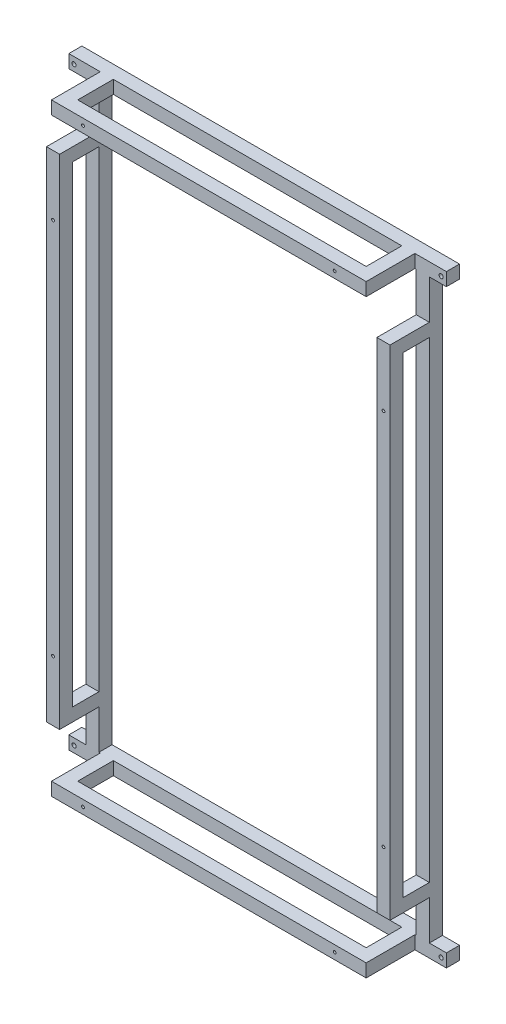
SolidWorks part; units mm, degrees
ref_plane "Plan de face" through (0, 0, 0) normal (0, 0, 1) x (1, 0, 0)
ref_plane "Plan de dessus" through (0, 0, 0) normal (0, 1, 0) x (1, 0, 0)
ref_plane "Plan de droite" through (0, 0, 0) normal (1, 0, 0) x (0, 0, -1)
sketch "Esquisse1" plane through (0, 0, 0) normal (0, 0, 1) x (1, 0, 0)
  line L1 (0, 0) -> (720, 0)
  line L2 (0, 0) -> (0, 25)
  line L3 (0, 25) -> (720, 25)
  line L4 (720, 0) -> (720, 25)
  line L5 (720, -1100) -> (0, -1100)
  line L6 (720, -1100) -> (720, -1125)
  line L7 (720, -1125) -> (0, -1125)
  line L8 (0, -1100) -> (0, -1125)
  point P9 (720, -1112.5)
  point P10 (720, 12.5)
  dimension "D1" = 25
  dimension "D2" = 720
  dimension "D3" = 720
  dimension "D4" = 0
  dimension "D5" = 25
  dimension "D6" = 1100
extrude "Boss.-Extru.1" add sketch "Esquisse1" along normal blind 25
sketch "Esquisse2" plane through (0, 0, 25) normal (0, 0, 1) x (1, 0, 0)
  line L0 (0, 25) -> (0, 0) construction
  line L1 (720, 0) -> (720, 25) construction
  line L2 (720, 25) -> (0, 25) construction
  line L4 (720, -1125) -> (720, -1100) construction
  line L5 (0, -1125) -> (720, -1125) construction
  line L6 (0, -1100) -> (0, -1125) construction
  circle A0 centre (10, 12.5) radius 4
  circle A1 centre (710, 12.5) radius 4
  circle A2 centre (710, -1112.5) radius 4
  circle A3 centre (10, -1112.5) radius 4
  point P22 (7.912, -1225)
  point P23 (0, 0)
  dimension "D2" = 8
  dimension "D3" = 8
  dimension "D7" = 8
  dimension "D8" = 8
  dimension "D1" = 700
  dimension "D4" = 10
  dimension "D5" = 10
  dimension "D6" = 12.5
  dimension "D9" = 10
  dimension "D10" = 12.5
  dimension "D11" = 10
  dimension "D12" = 12.5
extrude "Enlèv. mat.-Extru.1" cut sketch "Esquisse2" against normal blind 100 and the other way blind 25
sketch "Esquisse3" plane through (0, 0, 25) normal (0, 0, 1) x (1, 0, 0)
  line L0 (720, 25) -> (0, 25) construction
  line L1 (60, 25) -> (85, 25)
  line L2 (60, 25) -> (60, 0)
  line L3 (60, 0) -> (85, 0)
  line L4 (85, 25) -> (85, 0)
  line L5 (0, 0) -> (720, 0) construction
  line L6 (0, 25) -> (0, 0) construction
  line L7 (635, 0) -> (660, 0)
  line L8 (635, 0) -> (635, 25)
  line L9 (635, 25) -> (660, 25)
  line L10 (660, 0) -> (660, 25)
  line L11 (720, 0) -> (720, 25) construction
  line L12 (0, -1125) -> (720, -1125) construction
  line L13 (60, -1125) -> (85, -1125)
  line L14 (60, -1125) -> (60, -1100)
  line L15 (60, -1100) -> (85, -1100)
  line L16 (85, -1125) -> (85, -1100)
  line L17 (720, -1100) -> (0, -1100) construction
  line L19 (660, -1100) -> (635, -1100)
  line L20 (660, -1100) -> (660, -1125)
  line L21 (660, -1125) -> (635, -1125)
  line L22 (635, -1100) -> (635, -1125)
  point P16 (635, 12.5)
  dimension "D1" = 25
  dimension "D2" = 25
  dimension "D3" = 60
  dimension "D4" = 60
  dimension "D5" = 550
extrude "Boss.-Extru.2" add sketch "Esquisse3" along normal blind 68
sketch "Esquisse4" plane through (0, 0, 93) normal (0, 0, 1) x (1, 0, 0)
  line L1 (660, 25) -> (60, 25)
  line L2 (660, 25) -> (660, 0)
  line L3 (660, 0) -> (60, 0)
  line L4 (60, 25) -> (60, 0)
  line L5 (60, -1125) -> (660, -1125)
  line L6 (60, -1125) -> (60, -1100)
  line L7 (60, -1100) -> (660, -1100)
  line L8 (660, -1125) -> (660, -1100)
extrude "Boss.-Extru.3" add sketch "Esquisse4" along normal blind 25
sketch "Esquisse5" plane through (0, 0, 118) normal (0, 0, 1) x (1, 0, 0)
  line L0 (60, 0) -> (660, 0) construction
  line L1 (0, 25) -> (0, 0) construction
  line L2 (60, -1125) -> (660, -1125) construction
  line L3 (0, -1100) -> (0, -1125) construction
  line L4 (720, -1125) -> (720, -1100) construction
  circle A0 centre (120, 12.5) radius 2.75
  circle A1 centre (600, 12.5) radius 2.75
  circle A2 centre (600, -1112.5) radius 2.75
  circle A3 centre (120, -1112.5) radius 2.75
  dimension "D1" = 5.5
  dimension "D2" = 5.5
  dimension "D7" = 5.5
  dimension "D8" = 5.5
  dimension "D3" = 12.5
  dimension "D4" = 12.5
  dimension "D5" = 480
  dimension "D6" = 120
  dimension "D9" = 12.5
  dimension "D10" = 12.5
  dimension "D11" = 120
  dimension "D12" = 120
extrude "Enlèv. mat.-Extru.2" cut sketch "Esquisse5" against normal blind 25
sketch "Esquisse6" plane through (0, 0, 0) normal (0, 0, -1) x (-1, 0, 0)
  line L0 (-720, -1100) -> (0, -1100) construction
  line L1 (-687.5, -1100) -> (-662.5, -1100)
  line L2 (-687.5, -1100) -> (-687.5, 0)
  line L3 (-687.5, 0) -> (-662.5, 0)
  line L4 (-662.5, -1100) -> (-662.5, 0)
  line L5 (0, 0) -> (-720, 0) construction
  line L6 (-720, -1125) -> (-720, -1100) construction
  line L7 (-57.5, 0) -> (-32.5, 0)
  line L8 (-57.5, 0) -> (-57.5, -1100)
  line L9 (-57.5, -1100) -> (-32.5, -1100)
  line L10 (-32.5, 0) -> (-32.5, -1100)
  line L11 (0, -1100) -> (0, -1125) construction
  point P12 (-675, -1100)
  point P13 (-45, -1100)
  point P16 (-720, -1112.5)
  dimension "D1" = 25
  dimension "D2" = 25
  dimension "D3" = 630
  dimension "D4" = 45
  dimension "D5" = 45
extrude "Boss.-Extru.4" add sketch "Esquisse6" against normal blind 25
sketch "Esquisse7" plane through (0, 0, 25) normal (0, 0, 1) x (1, 0, 0)
  line L0 (32.5, -1100) -> (32.5, 0) construction
  line L1 (32.5, -1025) -> (57.5, -1025)
  line L2 (32.5, -1025) -> (32.5, -1000)
  line L3 (32.5, -1000) -> (57.5, -1000)
  line L4 (57.5, -1025) -> (57.5, -1000)
  line L5 (57.5, 0) -> (57.5, -1100) construction
  line L6 (662.5, -1100) -> (662.5, 0) construction
  line L7 (32.5, -100) -> (57.5, -100)
  line L8 (32.5, -100) -> (32.5, -75)
  line L9 (32.5, -75) -> (57.5, -75)
  line L10 (57.5, -100) -> (57.5, -75)
  line L11 (662.5, -100) -> (687.5, -100)
  line L12 (662.5, -100) -> (662.5, -75)
  line L13 (662.5, -75) -> (687.5, -75)
  line L14 (687.5, -100) -> (687.5, -75)
  line L15 (687.5, 0) -> (687.5, -1100) construction
  line L16 (660, -1125) -> (720, -1125) construction
  line L17 (662.5, -1025) -> (687.5, -1025)
  line L18 (662.5, -1025) -> (662.5, -1000)
  line L19 (662.5, -1000) -> (687.5, -1000)
  line L20 (687.5, -1025) -> (687.5, -1000)
  line L21 (720, 25) -> (660, 25) construction
  line L22 (0, -1125) -> (60, -1125) construction
  line L23 (60, 25) -> (0, 25) construction
  point P24 (675, -75)
  point P25 (32.5, -1012.5)
  point P26 (32.5, -87.5)
  point P27 (687.5, -1012.5)
  point P28 (687.5, -87.5)
  point P33 (690, 25)
  dimension "D1" = 25
  dimension "D2" = 25
  dimension "D3" = 25
  dimension "D4" = 25
  dimension "D5" = 925
  dimension "D6" = 925
  dimension "D7" = 1150
  dimension "D8" = 112.5
  dimension "D9" = 112.5
  dimension "D10" = 112.5
  dimension "D11" = 112.5
extrude "Boss.-Extru.5" add sketch "Esquisse7" along normal blind 50
sketch "Esquisse8" plane through (0, 0, 75) normal (0, 0, 1) x (1, 0, 0)
  line L1 (687.5, -1025) -> (662.5, -1025)
  line L2 (687.5, -1025) -> (687.5, -75)
  line L3 (687.5, -75) -> (662.5, -75)
  line L4 (662.5, -1025) -> (662.5, -75)
  line L5 (32.5, -75) -> (57.5, -75)
  line L6 (32.5, -75) -> (32.5, -1025)
  line L7 (32.5, -1025) -> (57.5, -1025)
  line L8 (57.5, -75) -> (57.5, -1025)
extrude "Boss.-Extru.6" add sketch "Esquisse8" along normal blind 25
sketch "Esquisse9" plane through (0, 0, 100) normal (0, 0, 1) x (1, 0, 0)
  line L0 (660, -1125) -> (720, -1125) construction
  line L1 (720, 25) -> (660, 25) construction
  line L2 (60, 25) -> (0, 25) construction
  line L3 (0, -1125) -> (60, -1125) construction
  line L4 (662.5, -75) -> (662.5, -1025) construction
  line L5 (57.5, -1025) -> (57.5, -75) construction
  line L6 (32.5, -75) -> (32.5, -1025) construction
  circle A0 centre (675, -910) radius 2.75
  circle A1 centre (45, -910) radius 2.75
  circle A2 centre (675, -190) radius 2.75
  circle A3 centre (45, -190) radius 2.75
  point P12 (690, 25)
  dimension "D1" = 5.5
  dimension "D2" = 5.5
  dimension "D3" = 5.5
  dimension "D4" = 5.5
  dimension "D5" = 720
  dimension "D6" = 720
  dimension "D7" = 1150
  dimension "D8" = 215
  dimension "D9" = 215
  dimension "D10" = 215
  dimension "D11" = 215
  dimension "D12" = 12.5
  dimension "D13" = 12.5
  dimension "D14" = 12.5
  dimension "D15" = 12.5
extrude "Enlèv. mat.-Extru.3" cut sketch "Esquisse9" against normal blind 25
